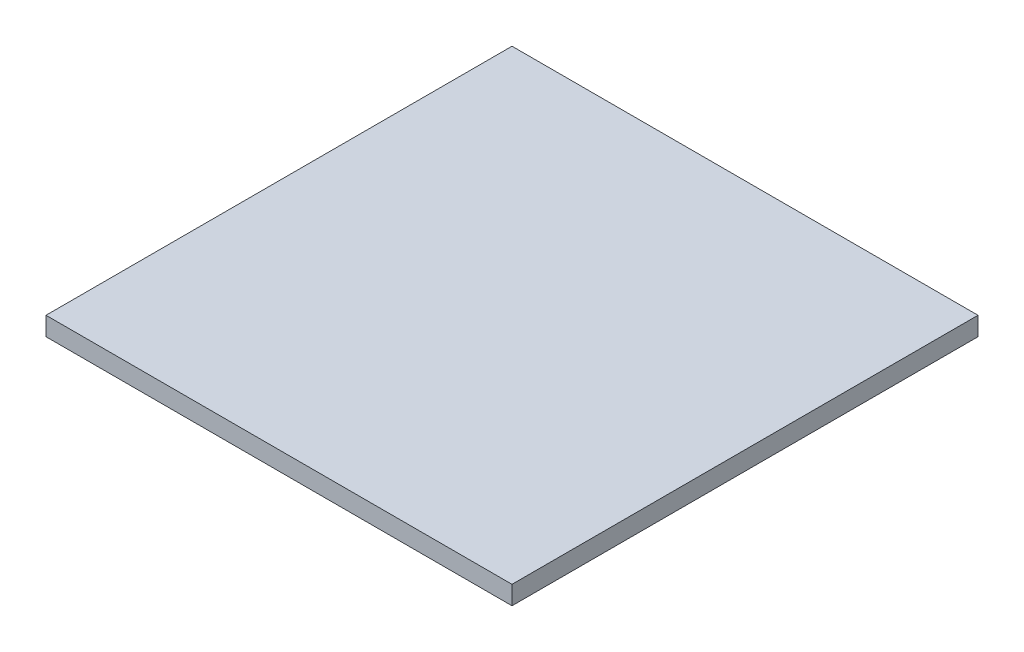
SolidWorks part; units mm, degrees
ref_plane "Front Plane" through (0, 0, 0) normal (0, 0, 1) x (1, 0, 0)
ref_plane "Top Plane" through (0, 0, 0) normal (0, 1, 0) x (1, 0, 0)
ref_plane "Right Plane" through (0, 0, 0) normal (1, 0, 0) x (0, 0, -1)
sketch "Sketch1" plane through (0, 0, 0) normal (0, 1, 0) x (1, 0, 0)
  line L1 (0, 0) -> (457.2, 0)
  line L2 (0, 0) -> (0, 457.2)
  line L3 (0, 457.2) -> (457.2, 457.2)
  line L4 (457.2, 0) -> (457.2, 457.2)
  dimension "D1" = 457.2
extrude "Boss-Extrude1" add sketch "Sketch1" along normal blind 18.2562
